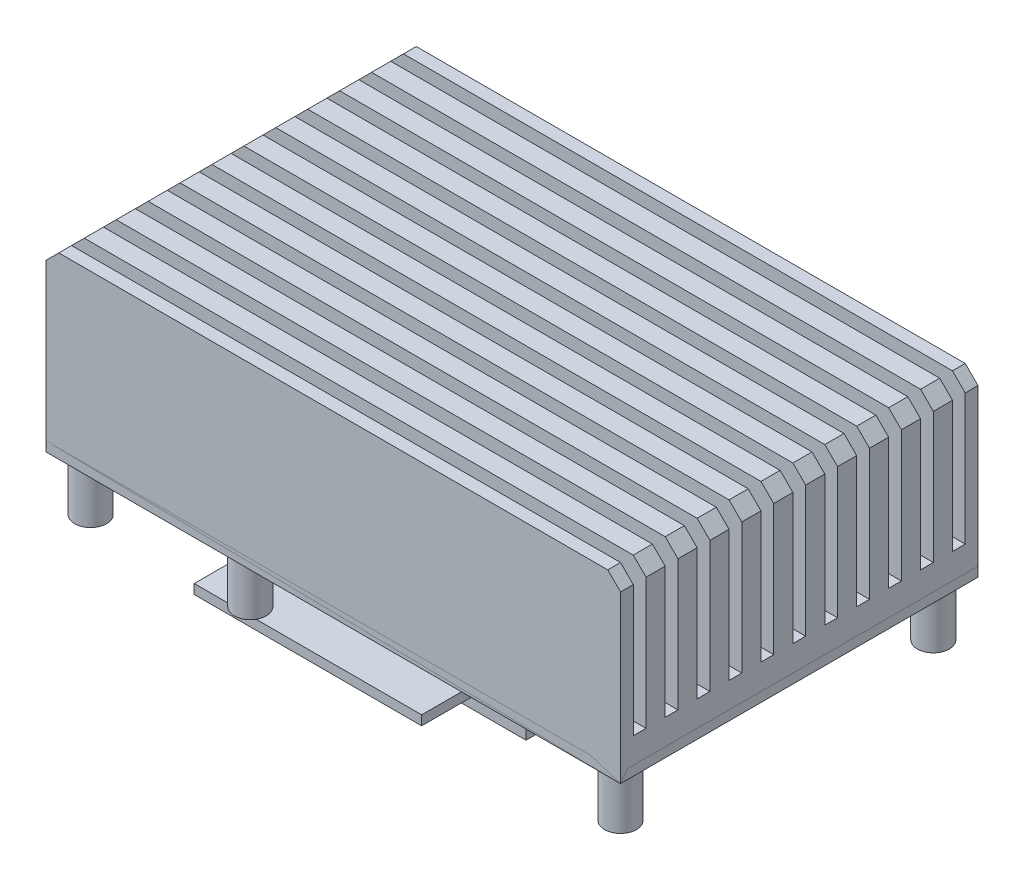
SolidWorks part; units mm, degrees
ref_plane "Front Plane" through (0, 0, 0) normal (0, 0, 1) x (1, 0, 0)
ref_plane "Top Plane" through (0, 0, 0) normal (0, 1, 0) x (1, 0, 0)
ref_plane "Right Plane" through (0, 0, 0) normal (1, 0, 0) x (0, 0, -1)
sketch "Sketch1" plane through (0, 0, 0) normal (0, 1, 0) x (1, 0, 0)
  line L1 (-45, 28) -> (45, 28)
  line L2 (-45, 28) -> (-45, -28)
  line L3 (-45, -28) -> (45, -28)
  line L4 (45, 28) -> (45, -28)
  line L5 (-45, 28) -> (45, -28) construction
  line L6 (-45, -28) -> (45, 28) construction
  point P0 (0, 0)
  dimension "D1" = 90
  dimension "D2" = 56
extrude "Boss-Extrude1" add sketch "Sketch1" along normal blind 1.5
sketch "Sketch2" plane through (0, 0, 0) normal (0, 1, 0) x (1, 0, 0)
  line L1 (-45, 28) -> (45, 28)
  line L2 (-45, 28) -> (-45, -28)
  line L3 (-45, -28) -> (45, -28)
  line L4 (45, 28) -> (45, -28)
extrude "Boss-Extrude2" add sketch "Sketch2" along normal blind 28 separate body
chamfer "Chamfer1" distance 2 angle 45 2 edges at (-45, 28, 0) (45, 28, 0)
sketch "Sketch3" plane through (0, 0, 0) normal (1, 0, 0) x (0, 0, -1)
  line L0 (-28, 28) -> (28, 28) construction
  line L1 (-26, 28) -> (-24, 28)
  line L2 (-26, 28) -> (-26, 5.4964)
  line L3 (-26, 5.4964) -> (-24, 5.4964)
  line L4 (-24, 28) -> (-24, 5.4964)
  line L5 (-28, 26) -> (-28, 0) construction
  dimension "D1" = 2
  dimension "D2" = 2
extrude "Cut-Extrude1" cut sketch "Sketch3" against normal through all both and the other way through all
pattern_linear "LPattern1" count 11 spacing 5 along (0, 0, -1) of "Cut-Extrude1"
sketch "Sketch4" plane through (0, 0, 0) normal (0, -1, 0) x (1, 0, 0)
  line L0 (-41.5, 24.5) -> (41.5, 24.5) construction
  line L1 (-41.5, 24.5) -> (-41.5, -24.5) construction
  line L2 (-41.5, 0) -> (-45, 0) construction
  line L3 (-45, -28) -> (-45, 28) construction
  line L4 (0, 24.5) -> (0, 28) construction
  line L5 (-45, 28) -> (45, 28) construction
  circle A0 centre (-41.5, 24.5) radius 1.5
  circle A1 centre (-41.5, 24.5) radius 2.5
  circle A2 centre (-16.5, 24.5) radius 1.5
  circle A3 centre (-16.5, 24.5) radius 2.5
  circle A4 centre (41.5, 24.5) radius 1.5
  circle A5 centre (41.5, 24.5) radius 2.5
  circle A6 centre (-41.5, -24.5) radius 2.5
  circle A7 centre (-41.5, -24.5) radius 1.5
  circle A8 centre (-16.5, -24.5) radius 1.5
  circle A9 centre (-16.5, -24.5) radius 2.5
  circle A10 centre (41.5, -24.5) radius 1.5
  circle A11 centre (41.5, -24.5) radius 2.5
  point P26 (0, 28)
  dimension "D1" = 3
  dimension "D2" = 1
  dimension "D3" = 25
  dimension "D4" = 58
  dimension "D5" = 49
extrude "Boss-Extrude3" add sketch "Sketch4" along normal blind 8.5 separate body
sketch "Sketch5" plane through (0, 0, 0) normal (0, 0, 1) x (1, 0, 0)
  line L1 (0, 8.5) -> (-14.5, 8.5)
  line L2 (0, 8.5) -> (0, 1.5)
  line L3 (0, 1.5) -> (-14.5, 1.5)
  line L4 (-14.5, 8.5) -> (-14.5, 1.5)
  line L5 (20.8, 8.1) -> (2.8, 8.1)
  line L6 (20.8, 8.1) -> (20.8, 1.5)
  line L7 (20.8, 1.5) -> (2.8, 1.5)
  line L8 (2.8, 8.1) -> (2.8, 1.5)
  line L9 (-45, 1.5) -> (45, 1.5) construction
  line L10 (45, 1.5) -> (45, 0) construction
  dimension "D1" = 14.5
  dimension "D2" = 7
  dimension "D3" = 18
  dimension "D4" = 6.6
  dimension "D5" = 24.2
  dimension "D6" = 45
sketch "Sketch6" plane through (0, 0, 0) normal (0, 1, 0) x (1, 0, 0)
  line L1 (-24.0358, -25.744) -> (11.5884, -25.744)
  line L2 (-24.0358, -25.744) -> (-24.0358, -2.0672)
  line L3 (-24.0358, -2.0672) -> (11.5884, -2.0672)
  line L4 (11.5884, -25.744) -> (11.5884, -2.0672)
extrude "Boss-Extrude4" add sketch "Sketch6" against normal blind 1.5 from offset 8.5 separate body offset against normal yes
sketch "Sketch7" plane through (0, -10, 0) normal (0, -1, 0) x (1, 0, 0)
  line L0 (11.5884, 2.0672) -> (-24.0358, 2.0672) construction
  line L1 (-22.2481, 7.5177) -> (9.7134, 7.5177)
  line L2 (-22.2481, 7.5177) -> (-22.2481, 2.0672)
  line L3 (-22.2481, 2.0672) -> (9.7134, 2.0672)
  line L4 (9.7134, 7.5177) -> (9.7134, 2.0672)
extrude "Boss-Extrude5" add sketch "Sketch7" along normal offset from surface (12 mm away) 50 separate body up to face at (0, 28, 27)
extrude "Boss-Extrude6" add sketch "Sketch5" against normal offset from surface (29 mm away) 1 separate body up to face at (0, 18, -28) offset beyond the face yes
sketch "Sketch9" plane through (0, 0, 0) normal (0, 0, 1) x (1, 0, 0)
  line L0 (-45, 26) -> (-45, 0) construction
  line L1 (45, 26) -> (45, 0) construction
  line L2 (45, 1.5) -> (-45, 1.5) construction
  circle A0 centre (36.5, 3.5) radius 1.25
  circle A1 centre (-36.5, 2) radius 1
  dimension "D1" = 8.5
  dimension "D3" = 2.5
  dimension "D4" = 2
  dimension "D6" = 2
  dimension "D2" = 8.5
  dimension "D5" = 0.5
extrude "Boss-Extrude7" add sketch "Sketch9" against normal offset from surface (28.3 mm away) 0.3 separate body up to face at (0, 18, -28) offset beyond the face yes
